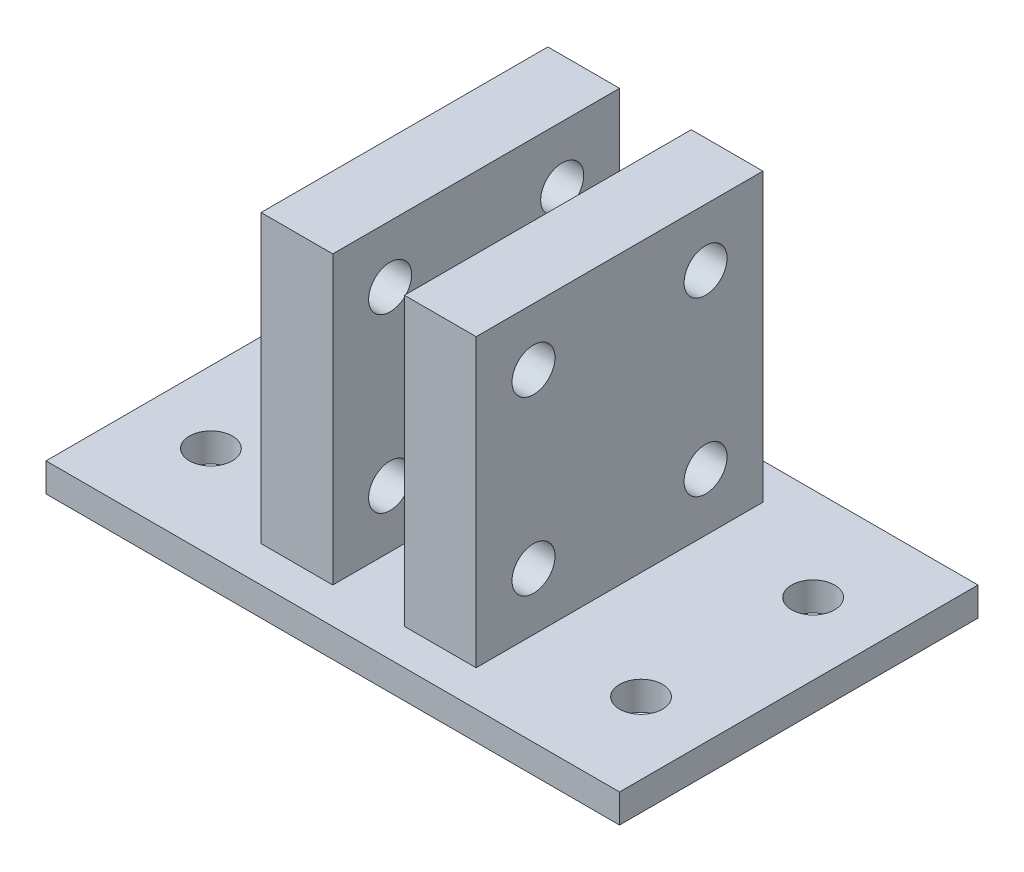
SolidWorks part; units mm, degrees
ref_plane "前视基准面" through (0, 0, 0) normal (0, 0, 1) x (1, 0, 0)
ref_plane "上视基准面" through (0, 0, 0) normal (0, 1, 0) x (1, 0, 0)
ref_plane "右视基准面" through (0, 0, 0) normal (1, 0, 0) x (0, 0, -1)
sketch "草图1" plane through (0, 0, 0) normal (0, 1, 0) x (1, 0, 0)
  line L1 (-20, 12.5) -> (20, 12.5)
  line L2 (-20, 12.5) -> (-20, -12.5)
  line L3 (-20, -12.5) -> (20, -12.5)
  line L4 (20, 12.5) -> (20, -12.5)
  line L5 (-20, 12.5) -> (20, -12.5) construction
  line L6 (-20, -12.5) -> (20, 12.5) construction
  point P0 (0, 0)
extrude "凸台-拉伸2" add sketch "草图1" along normal blind 2
sketch "草图3" plane through (0, 2, 0) normal (0, 1, 0) x (1, 0, 0)
  line L1 (-7.5, 10) -> (7.5, 10)
  line L2 (-7.5, 10) -> (-7.5, -10)
  line L3 (-7.5, -10) -> (7.5, -10)
  line L4 (7.5, 10) -> (7.5, -10)
  line L5 (-7.5, 10) -> (7.5, -10) construction
  line L6 (-7.5, -10) -> (7.5, 10) construction
  point P0 (0, 0)
  dimension "D1" = 15
  dimension "D2" = 20
extrude "凸台-拉伸3" add sketch "草图3" along normal blind 20
sketch "草图4" plane through (0, 22, 0) normal (0, 1, 0) x (1, 0, 0)
  line L0 (-7.5, -10) -> (7.5, -10) construction
  line L1 (-2.5, 10) -> (2.5, 10)
  line L2 (-2.5, 10) -> (-2.5, -10)
  line L3 (-2.5, -10) -> (2.5, -10)
  line L4 (2.5, 10) -> (2.5, -10)
  line L5 (-2.5, 10) -> (2.5, -10) construction
  line L6 (-2.5, -10) -> (2.5, 10) construction
  point P0 (0, 0)
  dimension "D1" = 5
extrude "切除-拉伸1" cut sketch "草图4" against normal blind 20
sketch "草图5" plane through (7.5, 0, 0) normal (1, 0, 0) x (0, 0, -1)
  line L0 (-10, 22) -> (10, 22) construction
  line L1 (-6, 18) -> (6, 18) construction
  line L2 (-6, 18) -> (-6, 6) construction
  line L3 (-6, 6) -> (6, 6) construction
  line L4 (6, 18) -> (6, 6) construction
  line L5 (-6, 18) -> (6, 6) construction
  line L6 (-6, 6) -> (6, 18) construction
  line L7 (-10, 22) -> (-10, 2) construction
  circle A0 centre (-6, 18) radius 1.5
  circle A1 centre (6, 18) radius 1.5
  circle A2 centre (-6, 6) radius 1.5
  circle A3 centre (6, 6) radius 1.5
  point P0 (0, 12)
  dimension "D1" = 10
  dimension "D2" = 10
extrude "切除-拉伸2" cut sketch "草图5" against normal blind 15
sketch "草图6" plane through (0, 2, 0) normal (0, 1, 0) x (1, 0, 0)
  line L1 (-15, 6) -> (15, 6) construction
  line L2 (-15, 6) -> (-15, -6) construction
  line L3 (-15, -6) -> (15, -6) construction
  line L4 (15, 6) -> (15, -6) construction
  line L5 (-15, 6) -> (15, -6) construction
  line L6 (-15, -6) -> (15, 6) construction
  circle A0 centre (-15, 6) radius 1.5
  circle A1 centre (-15, -6) radius 1.5
  circle A2 centre (15, 6) radius 1.5
  circle A3 centre (15, -6) radius 1.5
  point P0 (0, 0)
  dimension "D1" = 30
  dimension "D2" = 3
  dimension "D3" = 3
  dimension "D4" = 3
  dimension "D5" = 3
  dimension "D6" = 12
extrude "切除-拉伸3" cut sketch "草图6" against normal blind 15
